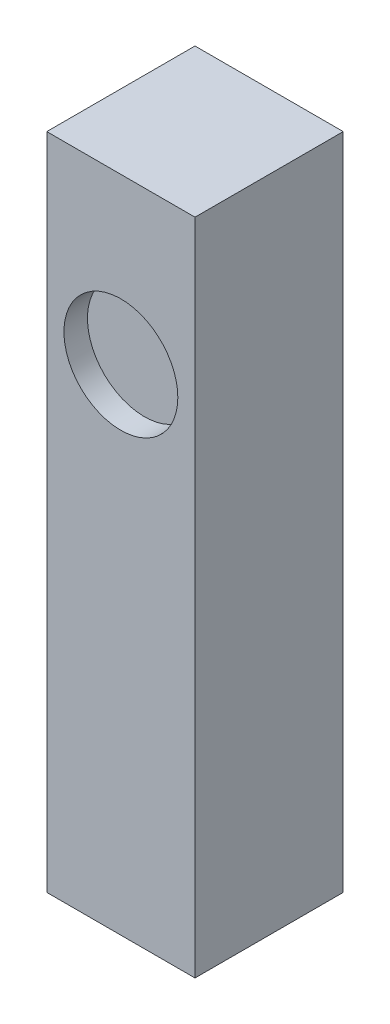
SolidWorks part; units mm, degrees
ref_plane "Front Plane" through (0, 0, 0) normal (0, 0, 1) x (1, 0, 0)
ref_plane "Top Plane" through (0, 0, 0) normal (0, 1, 0) x (1, 0, 0)
ref_plane "Right Plane" through (0, 0, 0) normal (1, 0, 0) x (0, 0, -1)
sketch "Sketch1" plane through (0, 0, 0) normal (0, 1, 0) x (1, 0, 0)
  line L1 (0, -58.2549) -> (0, 58.2549) construction
  line L5 (-58.2549, 0) -> (58.2549, 0) construction
  line L6 (0, 80) -> (-80, 80)
  line L7 (-80, 80) -> (-80, 0)
  line L8 (-80, 0) -> (-80, -80)
  line L9 (-80, -80) -> (0, -80)
  line L10 (80, 0) -> (80, -80)
  line L11 (80, -80) -> (0, -80)
  line L12 (80, 0) -> (80, 80)
  line L13 (80, 80) -> (0, 80)
  circle A0 centre (0, 0) radius 72.136
  point P16 (-80, 0)
  point P17 (0, 80)
  point P18 (80, 0)
  point P19 (0, -80)
extrude "Boss-Extrude1" add sketch "Sketch1" along normal blind 711.2 contours L8 L9 L11 L10 L12 L13 L6 L7
sketch "Sketch3" plane through (0, 0, 80) normal (0, 0, 1) x (1, 0, 0)
  line L0 (80, 711.2) -> (80, 0) construction
  line L1 (-80, 711.2) -> (-80, 0) construction
  line L2 (-80, 711.2) -> (80, 711.2) construction
  circle A0 centre (0, 533.4) radius 61.468
  point P0 (80, 355.6)
  point P1 (0, 533.4)
  point P4 (-80, 355.6)
  point P5 (-218.4995, 215.1229)
  dimension "D1" = 177.8
extrude "Cut-Extrude1" cut sketch "Sketch3" against normal blind 25.4
